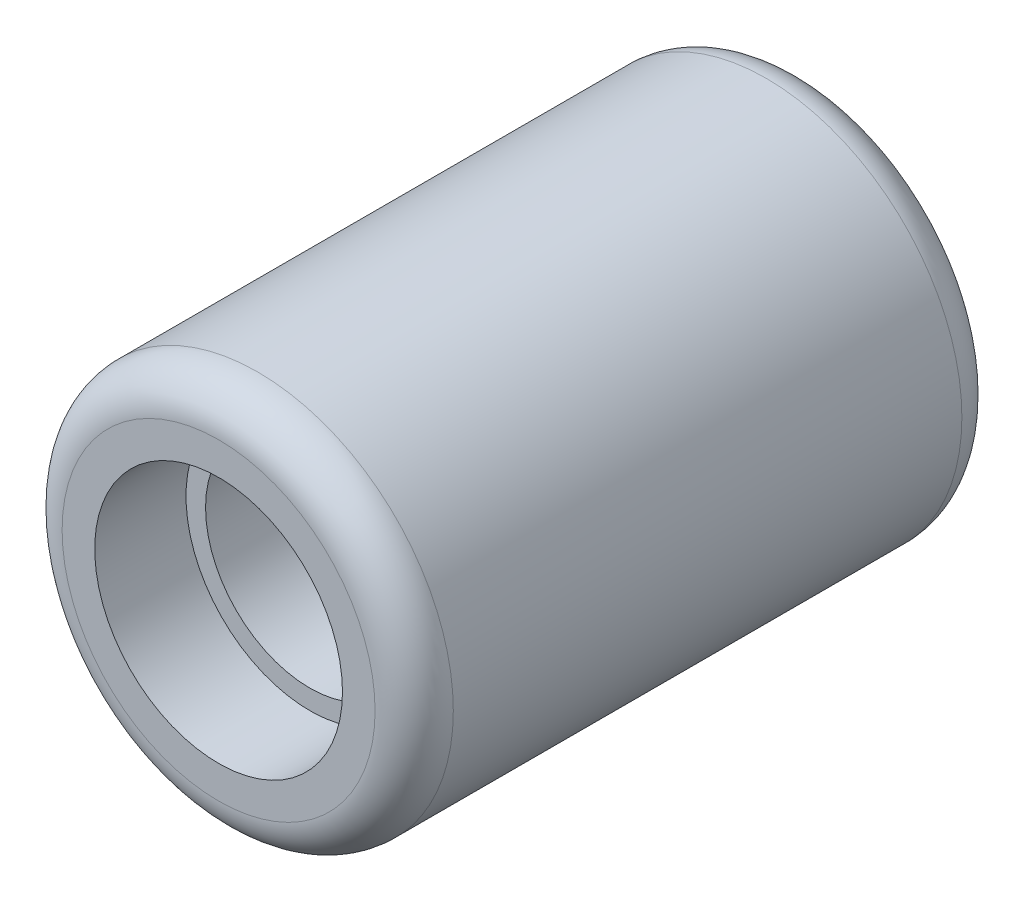
SolidWorks part; units mm, degrees
ref_plane "Plan de face" through (0, 0, 0) normal (0, 0, 1) x (1, 0, 0)
ref_plane "Plan de dessus" through (0, 0, 0) normal (0, 1, 0) x (1, 0, 0)
ref_plane "Plan de droite" through (0, 0, 0) normal (1, 0, 0) x (0, 0, -1)
sketch "Esquisse1" plane through (0, 0, 0) normal (0, 0, 1) x (1, 0, 0)
  circle A0 centre (0, 0) radius 15
  dimension "D1" = 30
extrude "Boss.-Extru.1" add sketch "Esquisse1" along normal blind 45
sketch "Esquisse4" plane through (0, 0, 45) normal (0, 0, 1) x (1, 0, 0)
  circle A0 centre (0, 0) radius 9.5
  dimension "D1" = 19
extrude "Enlèv. mat.-Extru.3" cut sketch "Esquisse4" against normal blind 7
sketch "Esquisse5" plane through (0, 0, 0) normal (0, 0, -1) x (-1, 0, 0)
  circle A0 centre (0, 0) radius 9.5
  dimension "D1" = 19
extrude "Enlèv. mat.-Extru.4" cut sketch "Esquisse5" against normal blind 7
sketch "Esquisse6" plane through (0, 0, 7) normal (0, 0, -1) x (-1, 0, 0)
  circle A0 centre (0, 0) radius 8
  dimension "D1" = 16
extrude "Enlèv. mat.-Extru.5" cut sketch "Esquisse6" against normal blind 60
fillet "Congé1" radius 3 2 edges at (15, 0, 45) (15, 0, 0)
